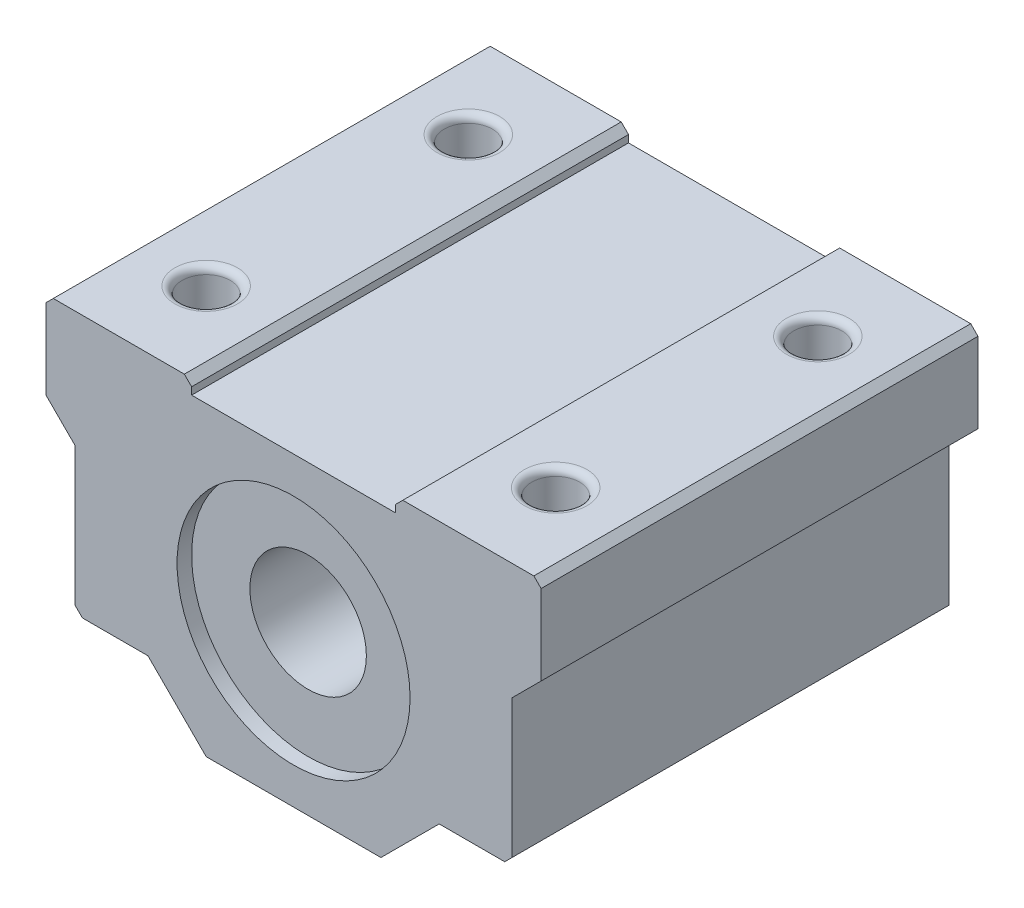
SolidWorks part; units mm, degrees
ref_plane "Front Plane" through (0, 0, 0) normal (0, 0, 1) x (1, 0, 0)
ref_plane "Top Plane" through (0, 0, 0) normal (0, 1, 0) x (1, 0, 0)
ref_plane "Right Plane" through (0, 0, 0) normal (1, 0, 0) x (0, 0, -1)
sketch "Sketch1" plane through (0, 0, 0) normal (0, 0, 1) x (1, 0, 0)
  line L0 (-17, 11.5) -> (-7, 11.5)
  line L1 (-6, -10.5) -> (6, -10.5)
  line L2 (6, -10.5) -> (10, -6.5)
  line L3 (10, -6.5) -> (15, -6.5)
  line L4 (15, -6.5) -> (15, 3.5)
  line L5 (15, 3.5) -> (17, 5.5)
  line L6 (17, 5.5) -> (17, 11.5)
  line L7 (0, -10.5) -> (0, 10.5) construction
  line L8 (-6, -10.5) -> (-10, -6.5)
  line L9 (-10, -6.5) -> (-15, -6.5)
  line L10 (-15, -6.5) -> (-15, 3.5)
  line L11 (-15, 3.5) -> (-17, 5.5)
  line L12 (-17, 5.5) -> (-17, 11.5)
  line L13 (-7, 10.5) -> (7, 10.5)
  line L14 (-7, 10.5) -> (-7, 11.5)
  line L15 (7, 10.5) -> (7, 11.5)
  line L16 (7, 11.5) -> (17, 11.5)
  circle A0 centre (0, 0) radius 8
  point P18 (0, 0)
  dimension "D13" = 16
  dimension "D1" = 22
  dimension "D2" = 18
  dimension "D3" = 6
  dimension "D4" = 6
  dimension "D5" = 18
  dimension "D6" = 1
  dimension "D7" = 12
  dimension "D8" = 20
  dimension "D9" = 14
  dimension "D10" = 30
  dimension "D11" = 2
  dimension "D12" = 34
extrude "Boss-Extrude1" add sketch "Sketch1" along normal mid plane 30
sketch "Sketch2" plane through (0, 11.5, 0) normal (0, 1, 0) x (1, 0, 0)
  line L0 (12, 0) -> (-12, 0) construction
  line L1 (-12, 0) -> (-12, 9) construction
  line L2 (0, 0) -> (0, -15) construction
  line L3 (7, -15) -> (-7, -15) construction
  line L4 (12, 0) -> (12, 9) construction
  circle A0 centre (-12, 9) radius 1.65
  circle A1 centre (-12, -9) radius 1.65
  circle A2 centre (12, -9) radius 1.65
  circle A3 centre (12, 9) radius 1.65
  point P8 (0, -15)
  dimension "D1" = 3.3
  dimension "D2" = 9
  dimension "D3" = 12
extrude "Cut-Extrude1" cut sketch "Sketch2" against normal through all
sketch "Sketch3" plane through (0, 0, 0) normal (0, 0, 1) x (1, 0, 0)
  circle A0 centre (0, 0) radius 4
  circle A1 centre (0, 0) radius 8
  circle A2 centre (0, 0) radius 8 construction
  dimension "D1" = 8
extrude "Boss-Extrude2" add sketch "Sketch3" along normal mid plane 28
fillet "Fillet1" radius 0.5 4 edges at (12, 11.5, -10.65) (12, 11.5, 10.65) (-12, 11.5, -7.35) (-12, 11.5, 7.35)
chamfer "Chamfer1" distance 0.5 angle 45 6 edges at (15, -6.5, 0) (-15, -6.5, 0) (-17, 11.5, 0) (-7, 11.5, 0) (7, 11.5, 0) (17, 11.5, 0)
